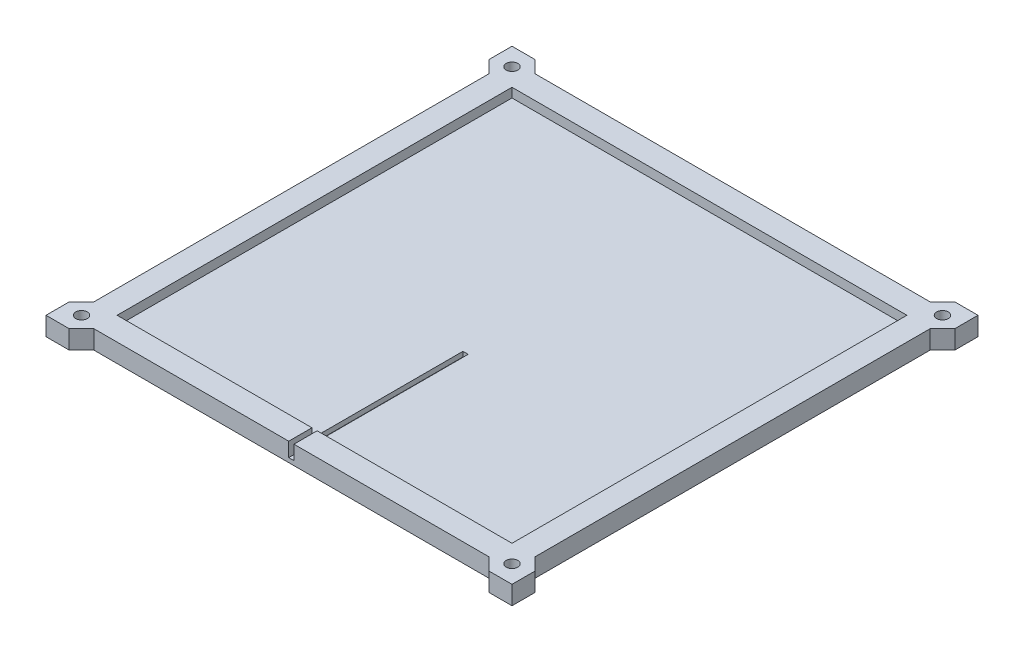
SolidWorks part; units mm, degrees
ref_plane "Front Plane" through (0, 0, 0) normal (0, 0, 1) x (1, 0, 0)
ref_plane "Top Plane" through (0, 0, 0) normal (0, 1, 0) x (1, 0, 0)
ref_plane "Right Plane" through (0, 0, 0) normal (1, 0, 0) x (0, 0, -1)
sketch "Sketch1" plane through (0, 0, 0) normal (0, 1, 0) x (1, 0, 0)
  line L1 (-190, -190) -> (190, -190)
  line L2 (-190, -190) -> (-190, 190)
  line L3 (-190, 190) -> (190, 190)
  line L4 (190, -190) -> (190, 190)
  line L5 (-190, -190) -> (190, 190) construction
  line L6 (-190, 190) -> (190, -190) construction
  point P0 (0, 0)
  dimension "D1" = 380
  dimension "D2" = 380
extrude "Boss-Extrude1" add sketch "Sketch1" along normal blind 8
sketch "Sketch2" plane through (0, 8, 0) normal (0, 1, 0) x (1, 0, 0)
  line L0 (170, 170) -> (-170, 170)
  line L1 (-170, 170) -> (-170, -170)
  line L2 (-170, -170) -> (170, -170)
  line L3 (170, -170) -> (170, 170)
  line L4 (190, -190) -> (190, 190)
  line L5 (190, 190) -> (-190, 190)
  line L6 (-190, 190) -> (-190, -190)
  line L7 (-190, -190) -> (190, -190)
  line L8 (190, -190) -> (190, 190)
  line L9 (190, 190) -> (-190, 190)
  line L10 (-190, 190) -> (-190, -190)
  line L11 (-190, -190) -> (190, -190)
  dimension "D1" = 0
  dimension "D2" = 20
extrude "Boss-Extrude2" add sketch "Sketch2" along normal blind 8
sketch "Sketch3" plane through (0, 16, 0) normal (0, 1, 0) x (1, 0, 0)
  line L4 (-190, -190) -> (190, -190)
  line L5 (190, -190) -> (190, 190)
  line L6 (190, 190) -> (-190, 190)
  line L7 (-190, 190) -> (-190, -190)
  line L8 (-190, -190) -> (190, -190)
  line L9 (190, -190) -> (190, 190)
  line L10 (190, 190) -> (-190, 190)
  line L11 (-190, 190) -> (-190, -190)
  line L22 (-170, 190) -> (-180.6066, 200.6066)
  line L23 (-180.6066, 200.6066) -> (-200.6066, 200.6066)
  line L24 (-200.6066, 200.6066) -> (-200.6066, 180.6066)
  line L25 (-200.6066, 180.6066) -> (-190, 170)
  line L26 (-190, 190) -> (-200.6066, 200.6066) construction
  circle A0 centre (-190, 190) radius 5 construction
  line M18 (-190, 190) -> (-190, -190)
  dimension "D6" = 10
  dimension "D2" = 135
  dimension "D3" = 15
  dimension "D5" = 20
  dimension "D1" = 0
extrude "Boss-Extrude3" add sketch "Sketch3" against normal up to surface (16 mm away) contours L24 L25 L10 L22 L23 M18 up to face at (0, 0, 0)
mirror "Mirror1" about plane through (0, 0, 0) normal (1, 0, 0) of "Boss-Extrude3"
mirror "Mirror2" about plane through (0, 0, 0) normal (0, 0, 1) of "Mirror1", "Boss-Extrude3"
sketch "Sketch6" plane through (0, 16, 0) normal (0, 1, 0) x (1, 0, 0)
  line L0 (-170, 170) -> (-200.6066, 200.6066) construction
  line L1 (0, 0) -> (0, 80.4196) construction
  line L2 (0, 0) -> (72.7459, 0) construction
  line L3 (170, 170) -> (200.6066, 200.6066) construction
  line L4 (170, -170) -> (200.6066, -200.6066) construction
  line L5 (-170, -170) -> (-200.6066, -200.6066) construction
  circle A2 centre (-185.3033, 185.3033) radius 5
  circle A3 centre (185.3033, 185.3033) radius 5
  circle A4 centre (185.3033, -185.3033) radius 5
  circle A5 centre (-185.3033, -185.3033) radius 5
  dimension "D1" = 10
extrude "Cut-Extrude1" cut sketch "Sketch6" against normal up to surface (16 mm away) up to face at (0, 0, 0)
sketch "Sketch8" plane through (0, 0, 190) normal (0, 0, 1) x (1, 0, 0)
  line L0 (0, 0) -> (0, 16) construction
  line L1 (-170, 16) -> (170, 16) construction
  line L2 (-2.25, 33.75) -> (2.25, 33.75)
  line L3 (-2.25, 33.75) -> (-2.25, 3.75)
  line L4 (2.25, 33.75) -> (2.25, 3.75)
  line L5 (-2.25, 3.75) -> (2.25, 3.75)
  line L6 (-170, 0) -> (170, 0) construction
  dimension "D1" = 4.5
  dimension "D2" = 30
  dimension "D3" = 3.75
extrude "Cut-Extrude2" cut sketch "Sketch8" against normal blind 150
